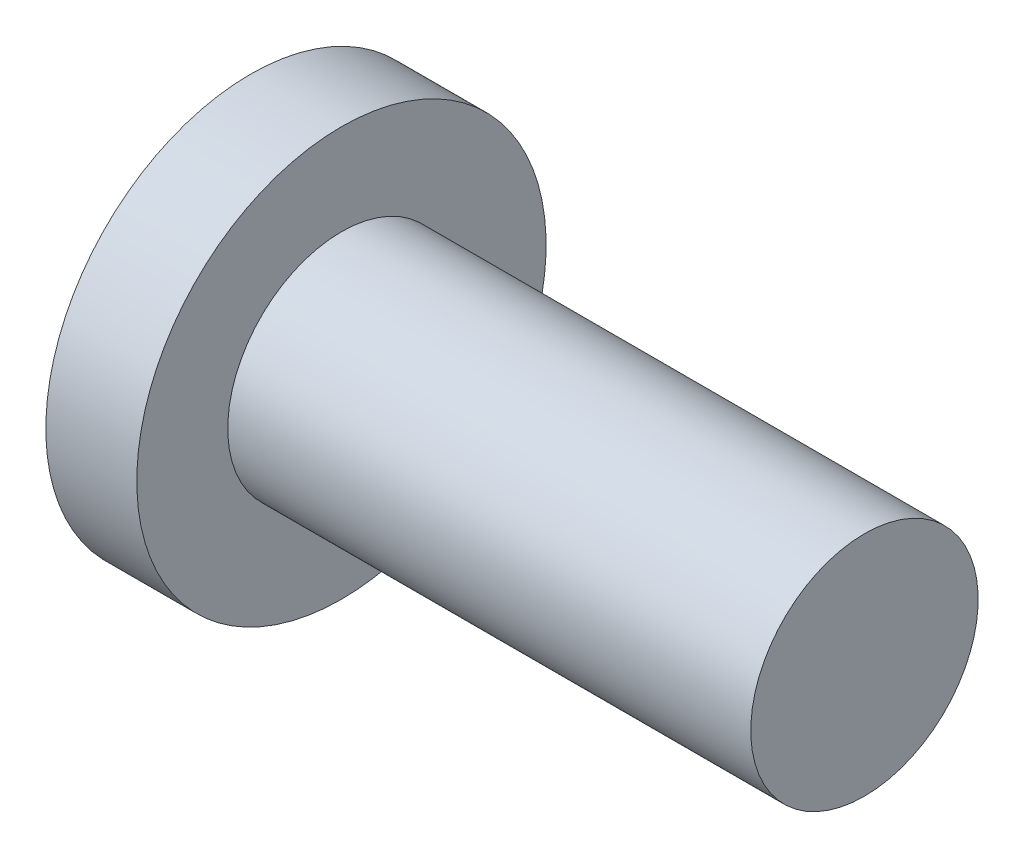
SolidWorks part; units mm, degrees
ref_plane "Front Plane" through (0, 0, 0) normal (0, 0, 1) x (1, 0, 0)
ref_plane "Top Plane" through (0, 0, 0) normal (0, 1, 0) x (1, 0, 0)
ref_plane "Right Plane" through (0, 0, 0) normal (1, 0, 0) x (0, 0, -1)
sketch "Sketch1" plane through (0, 0, 0) normal (0, 0, 1) x (1, 0, 0)
  line L0 (-441.0159, 0) -> (441.0159, 0) construction
  line L1 (54, 10) -> (8, 10)
  line L2 (8, 10) -> (8, 18)
  line L3 (8, 18) -> (0, 18)
  line L4 (0, 18) -> (0, 0)
  line L6 (54, 0) -> (54, 10)
  line L7 (0, 0) -> (54, 0)
  point P3 (0, 0)
  dimension "D1" = 46
  dimension "D2" = 20
  dimension "D3" = 36
  dimension "D4" = 8
revolve "Revolve1" add sketch "Sketch1" angle 360 about L0
